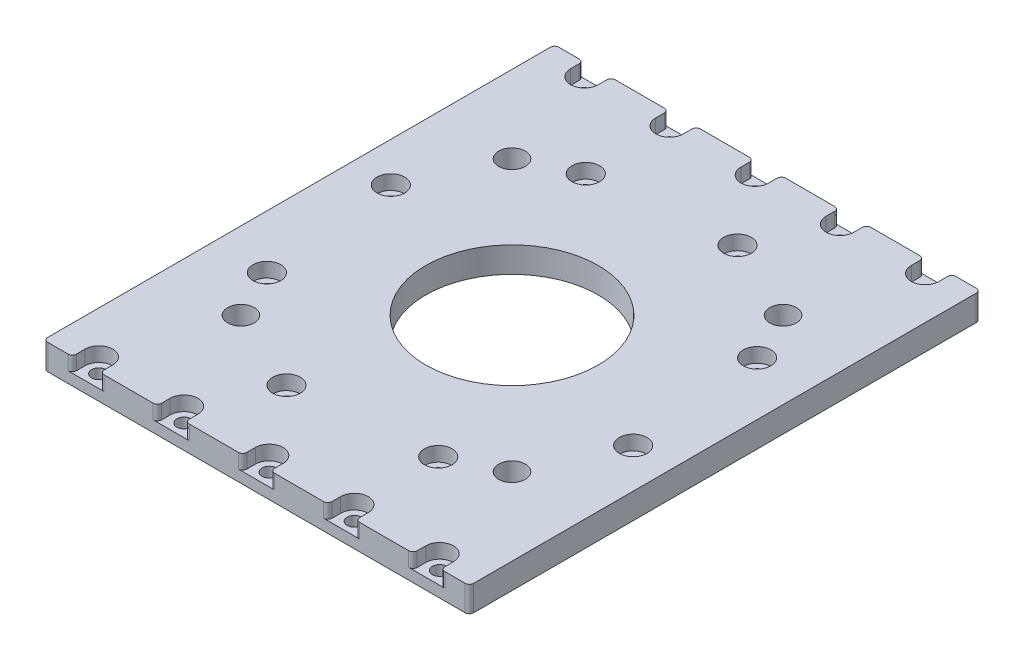
SolidWorks part; units mm, degrees
material "6061-T6 (SS)"
ref_plane "Front Plane" through (0, 0, 0) normal (0, 0, 1) x (1, 0, 0)
ref_plane "Top Plane" through (0, 0, 0) normal (0, 1, 0) x (1, 0, 0)
ref_plane "Right Plane" through (0, 0, 0) normal (1, 0, 0) x (0, 0, -1)
sketch "Sketch1" plane through (0, 0, 0) normal (0, 1, 0) x (1, 0, 0)
  circle A0 centre (0, 0) radius 50
  circle A1 centre (0, 0) radius 20.25
  dimension "D1" = 100
  dimension "D2" = 40.5
extrude "Boss-Extrude1" add sketch "Sketch1" along normal blind 6
sketch "Sketch2" plane through (0, 6, 0) normal (0, 1, 0) x (1, 0, 0)
  line L1 (-20.1161, 37.4379) -> (0, 0) construction
  circle A0 centre (0, 0) radius 42.5 construction
  point P4 (-20.1161, 37.4379)
  point P10 (12.2483, 40.6968)
  point P11 (37.4379, 20.1161)
  point P12 (40.6968, -12.2483)
  point P13 (20.1161, -37.4379)
  point P14 (-12.2483, -40.6968)
  point P15 (-37.4379, -20.1161)
  point P16 (-40.6968, 12.2483)
  dimension "D1" = 85
  dimension "D3" = 28.25
  dimension "D2" = 8
hole_wizard "CBORE for M3 Hex Socket Head Cap Screw2" positions "Sketch2" profile "Sketch3" counterbore size "M3" standard "DIN" end condition through all
sketch "Sketch3" plane through (-40.6968, 6, -12.2483) normal (1, 0, 0) x (0, 0, 1)
  line L0 (0, 0) -> (0, 6)
  line L1 (0, 6) -> (1.7, 6)
  line L3 (1.7, 6) -> (1.7, 3.4)
  line L4 (1.7, 3.4) -> (3.25, 3.4)
  line L5 (3.25, 3.4) -> (3.25, 0)
  line L7 (3.25, 0) -> (0, 0)
  line L11 (0, -6.35) -> (0, 107.95) construction
  dimension "Thru Hole Dia." = 3.4
  dimension "Thru Hole Depth" = 6
  dimension "C'Bore Dia." = 6.5
  dimension "C'Bore Depth" = 3.4
sketch "Sketch6" plane through (0, 6, 0) normal (0, 1, 0) x (1, 0, 0)
  line L0 (-50, 0) -> (-50, -60)
  line L1 (-50, -60) -> (50, -60)
  line L2 (50, -60) -> (50, 0)
  circle A0 centre (0, 0) radius 50 construction
  arc A1 (-50, 0) -> (50, 0) centre (0, 0) ccw
  dimension "D1" = 60
extrude "Boss-Extrude2" add sketch "Sketch6" against normal up to surface (6 mm away) up to face at (-20.1161, 0, -35.7379)
sketch "Sketch10" plane through (0, 6, 0) normal (0, 1, 0) x (1, 0, 0)
  line L0 (-50, 0) -> (-50, 60)
  line L1 (-50, 60) -> (50, 60)
  line L2 (50, 60) -> (50, 0)
  arc A0 (50, 0) -> (-50, 0) centre (0, 0) ccw construction
  arc A1 (50, 0) -> (-50, 0) centre (0, 0) ccw
  dimension "D1" = 60
extrude "Boss-Extrude3" add sketch "Sketch10" against normal up to surface (6 mm away) up to face at (-20.1161, 0, -35.7379)
sketch "Sketch11" plane through (0, 6, 0) normal (0, 1, 0) x (1, 0, 0)
  line L0 (50, 60) -> (-50, 60) construction
  line L3 (0, 0) -> (0, 57) construction
  line L4 (0, 0) -> (-50000, 0) construction
  point P0 (-40, 57)
  point P13 (-20, 57)
  point P14 (0, 57)
  point P15 (20, 57)
  point P16 (40, 57)
  point P57 (40, -57)
  point P58 (20, -57)
  point P59 (0, -57)
  point P60 (-20, -57)
  point P61 (-40, -57)
  dimension "D1" = 3
  dimension "D2" = 5
  dimension "D5" = 20
hole_wizard "CBORE for M3 Hex Socket Head Cap Screw1" positions "Sketch11" profile "Sketch12" counterbore size "M3" standard "DIN" end condition through all
sketch "Sketch12" plane through (-40, 6, -57) normal (1, 0, 0) x (0, 0, 1)
  line L0 (0, 0) -> (0, 6)
  line L1 (0, 6) -> (1.7, 6)
  line L3 (1.7, 6) -> (1.7, 3.4)
  line L4 (1.7, 3.4) -> (3.25, 3.4)
  line L5 (3.25, 3.4) -> (3.25, 0)
  line L7 (3.25, 0) -> (0, 0)
  line L11 (0, -6.35) -> (0, 107.95) construction
  dimension "Thru Hole Dia." = 3.4
  dimension "Thru Hole Depth" = 6
  dimension "C'Bore Dia." = 6.5
  dimension "C'Bore Depth" = 3.4
sketch "Sketch13" plane through (0, 6, 0) normal (0, 1, 0) x (1, 0, 0)
  line L0 (-43.25, 57) -> (-43.25, 60)
  line L1 (-41.25, 60) -> (-50, 60) construction
  line L2 (-43.25, 60) -> (-36.75, 60)
  line L3 (-21.25, 60) -> (-38.75, 60) construction
  line L4 (-36.75, 60) -> (-36.75, 57)
  line L5 (-23.25, 57) -> (-23.25, 60)
  line L6 (-23.25, 60) -> (-16.75, 60)
  line L7 (-16.75, 60) -> (-16.75, 57)
  line L8 (-3.25, 57) -> (-3.25, 60)
  line L9 (-3.25, 60) -> (3.25, 60)
  line L10 (3.25, 60) -> (3.25, 57)
  line L11 (16.75, 57) -> (16.75, 60)
  line L12 (16.75, 60) -> (23.25, 60)
  line L13 (23.25, 60) -> (23.25, 57)
  line L14 (36.75, 57) -> (36.75, 60)
  line L15 (36.75, 60) -> (43.25, 60)
  line L16 (43.25, 60) -> (43.25, 57)
  line L17 (0, 0) -> (69.1463, 0) construction
  line L18 (43.25, -60) -> (43.25, -57)
  line L19 (36.75, -60) -> (43.25, -60)
  line L20 (36.75, -57) -> (36.75, -60)
  line L21 (23.25, -60) -> (23.25, -57)
  line L22 (16.75, -60) -> (23.25, -60)
  line L23 (16.75, -57) -> (16.75, -60)
  line L24 (3.25, -60) -> (3.25, -57)
  line L25 (-3.25, -60) -> (3.25, -60)
  line L26 (-3.25, -57) -> (-3.25, -60)
  line L27 (-16.75, -60) -> (-16.75, -57)
  line L28 (-23.25, -60) -> (-16.75, -60)
  line L29 (-23.25, -57) -> (-23.25, -60)
  line L30 (-36.75, -60) -> (-36.75, -57)
  line L31 (-43.25, -60) -> (-36.75, -60)
  line L32 (-43.25, -57) -> (-43.25, -60)
  arc A0 (-41.25, 60) -> (-38.75, 60) centre (-40, 57) ccw construction
  arc A1 (-43.25, 57) -> (-36.75, 57) centre (-40, 57) ccw
  arc A2 (-23.25, 57) -> (-16.75, 57) centre (-20, 57) ccw
  arc A3 (-3.25, 57) -> (3.25, 57) centre (0, 57) ccw
  arc A4 (16.75, 57) -> (23.25, 57) centre (20, 57) ccw
  arc A5 (36.75, 57) -> (43.25, 57) centre (40, 57) ccw
  arc A6 (36.75, -57) -> (43.25, -57) centre (40, -57) cw
  arc A7 (16.75, -57) -> (23.25, -57) centre (20, -57) cw
  arc A8 (-3.25, -57) -> (3.25, -57) centre (0, -57) cw
  arc A9 (-23.25, -57) -> (-16.75, -57) centre (-20, -57) cw
  arc A10 (-43.25, -57) -> (-36.75, -57) centre (-40, -57) cw
  dimension "D1" = 5
extrude "Cut-Extrude1" cut sketch "Sketch13" against normal up to surface (3.4 mm away) up to face at (-40, 2.6, -56.875)
fillet "Fillet1" radius 1 24 edges at (-43.25, 4.3, 60) (-50, 3, 60) (-50, 3, -60) (-36.75, 4.3, -60) (-23.25, 4.3, -60) (-16.75, 4.3, -60) (-3.25, 4.3, -60) (3.25, 4.3, -60) (16.75, 4.3, -60) (23.25, 4.3, -60) (36.75, 4.3, -60) (43.25, 4.3, -60) (50, 3, -60) (50, 3, 60) (43.25, 4.3, 60) (36.75, 4.3, 60) (23.25, 4.3, 60) (16.75, 4.3, 60) (3.25, 4.3, 60) (-3.25, 4.3, 60) (-16.75, 4.3, 60) (-23.25, 4.3, 60) (-36.75, 4.3, 60) (-43.25, 4.3, -60)
sketch "Sketch15" plane through (0, 6, 0) normal (0, 1, 0) x (1, 0, 0)
  line L0 (0, 0) -> (31.8198, 31.8198) construction
  line L1 (0, 0) -> (31.8198, -31.8198) construction
  line L2 (0, 0) -> (-31.8198, -31.8198) construction
  line L3 (0, 0) -> (-31.8198, 31.8198) construction
  circle A0 centre (0, 0) radius 45
  point P7 (31.8198, 31.8198)
  point P8 (31.8198, -31.8198)
  point P9 (-31.8198, -31.8198)
  point P10 (-31.8198, 31.8198)
  point P11 (0, 0)
  point P19 (-31.8198, 31.8198)
  point P21 (-31.8198, -31.8198)
  point P23 (31.8198, -31.8198)
  dimension "D1" = 90
  dimension "D2" = 45
  dimension "D3" = 4
hole_wizard "Tap Drill for M6 Helicoil1" positions "Sketch15" profile "Sketch16" hole size "M6x1.0" standard "DIN" end condition through all
sketch "Sketch16" plane through (31.8198, 6, 31.8198) normal (1, 0, 0) x (0, 0, 1)
  line L0 (0, 0) -> (0, 6)
  line L1 (0, 6) -> (3.125, 6)
  line L2 (3.125, 6) -> (3.125, 0)
  line L5 (3.125, 0) -> (0, 0)
  line L11 (0, -6.35) -> (0, 107.95) construction
  dimension "Thru Hole Dia." = 6.25
  dimension "Thru Hole Depth" = 6
